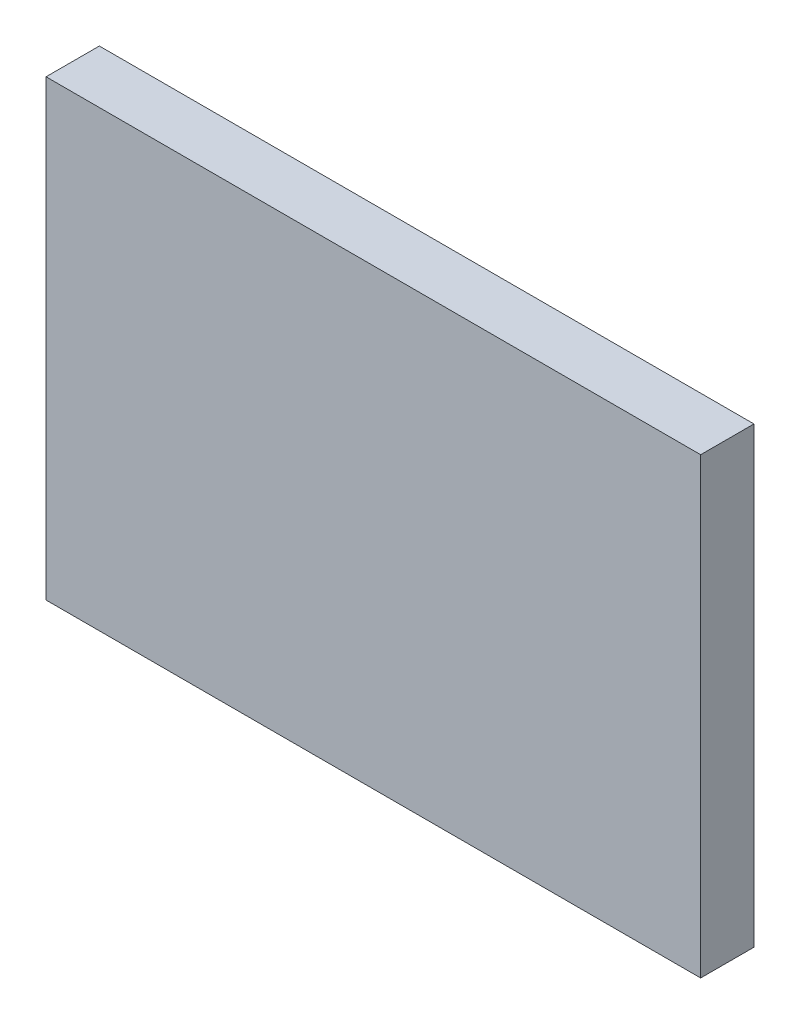
SolidWorks part; units mm, degrees
ref_plane "Front Plane" through (0, 0, 0) normal (0, 0, 1) x (1, 0, 0)
ref_plane "Top Plane" through (0, 0, 0) normal (0, 1, 0) x (1, 0, 0)
ref_plane "Right Plane" through (0, 0, 0) normal (1, 0, 0) x (0, 0, -1)
sketch "Sketch1" plane through (0, 0, 0) normal (0, 0, 1) x (1, 0, 0)
  line L1 (19.5, -13.5) -> (-19.5, -13.5)
  line L2 (19.5, -13.5) -> (19.5, 13.5)
  line L3 (19.5, 13.5) -> (-19.5, 13.5)
  line L4 (-19.5, -13.5) -> (-19.5, 13.5)
  line L5 (19.5, -13.5) -> (-19.5, 13.5) construction
  line L6 (19.5, 13.5) -> (-19.5, -13.5) construction
  point P0 (0, 0)
  dimension "D1" = 39
  dimension "D2" = 27
extrude "Boss-Extrude1" add sketch "Sketch1" along normal blind 3.175
